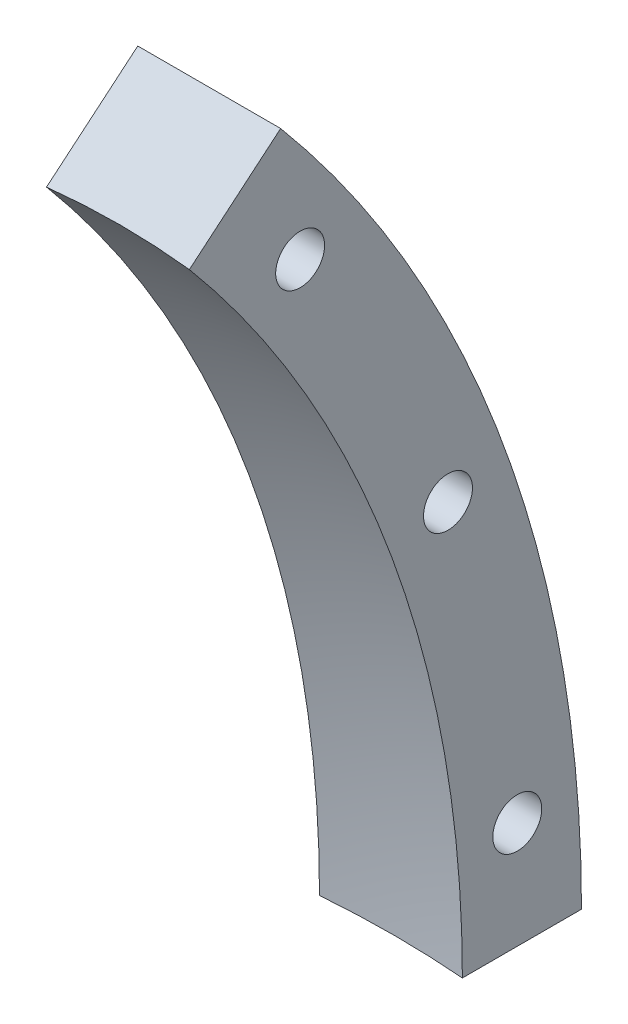
SolidWorks part; units mm, degrees
material "ABS"
ref_plane "Front Plane" through (0, 0, 0) normal (0, 0, 1) x (1, 0, 0)
ref_plane "Top Plane" through (0, 0, 0) normal (0, 1, 0) x (1, 0, 0)
ref_plane "Right Plane" through (0, 0, 0) normal (1, 0, 0) x (0, 0, -1)
sketch "Sketch1" plane through (0, 0, 0) normal (0, 1, 0) x (1, 0, 0)
  line L0 (0, 0) -> (0, 152.4) construction
  line L1 (0, 152.4) -> (-9.525, 152.4)
  line L2 (0, 152.4) -> (9.525, 152.4)
  line L3 (-9.525, 152.4) -> (-9.525, 171.45)
  line L4 (-9.525, 171.45) -> (9.525, 171.45)
  line L5 (9.525, 171.45) -> (9.525, 152.4)
  line L6 (0, 0) -> (51.6889, 0) construction
  dimension "D1" = 152.4
  dimension "D2" = 9.525
  dimension "D3" = 9.525
  dimension "D4" = 19.05
revolve "Revolve1" add sketch "Sketch1" angle 40 about L6
sketch "Sketch2" plane through (0, 0, 0) normal (0, 1, 0) x (1, 0, 0)
  line L0 (0, 0) -> (0, 38.1) construction
  line L1 (0, 0) -> (16.2842, 0) construction
  line L2 (-117.856, 38.1) -> (117.856, 38.1)
  arc A0 (117.856, 38.1) -> (-117.856, 38.1) centre (0, 38.1) ccw
  dimension "D2" = 235.712
  dimension "D1" = 38.1
revolve "Cut-Revolve1" cut sketch "Sketch2" angle 360 about L1
sketch "Sketch3" plane through (9.525, 0, 0) normal (1, 0, 0) x (0, 0, -1)
  line L0 (0, 0) -> (163.5102, 0) construction
  line L1 (155.5705, 0) -> (171.45, 0) construction
  line L2 (119.1739, 99.9988) -> (131.3383, 110.2059) construction
  line L3 (0, 0) -> (133.9397, 93.7856) construction
  line L4 (0, 0) -> (153.6494, 55.9238) construction
  line L5 (0, 0) -> (162.888, 14.2509) construction
  arc A0 (163.5102, 0) -> (125.2561, 105.1024) centre (0, 0) ccw construction
  circle A1 centre (162.888, 14.2509) radius 3.2639
  circle A2 centre (153.6494, 55.9238) radius 3.2639
  circle A3 centre (133.9397, 93.7856) radius 3.2639
  dimension "D1" = 6.5278
  dimension "D2" = 6.5278
  dimension "D3" = 6.5278
  dimension "D4" = 5
  dimension "D5" = 5
  dimension "D6" = 15
extrude "Cut-Extrude1" cut sketch "Sketch3" against normal through all
